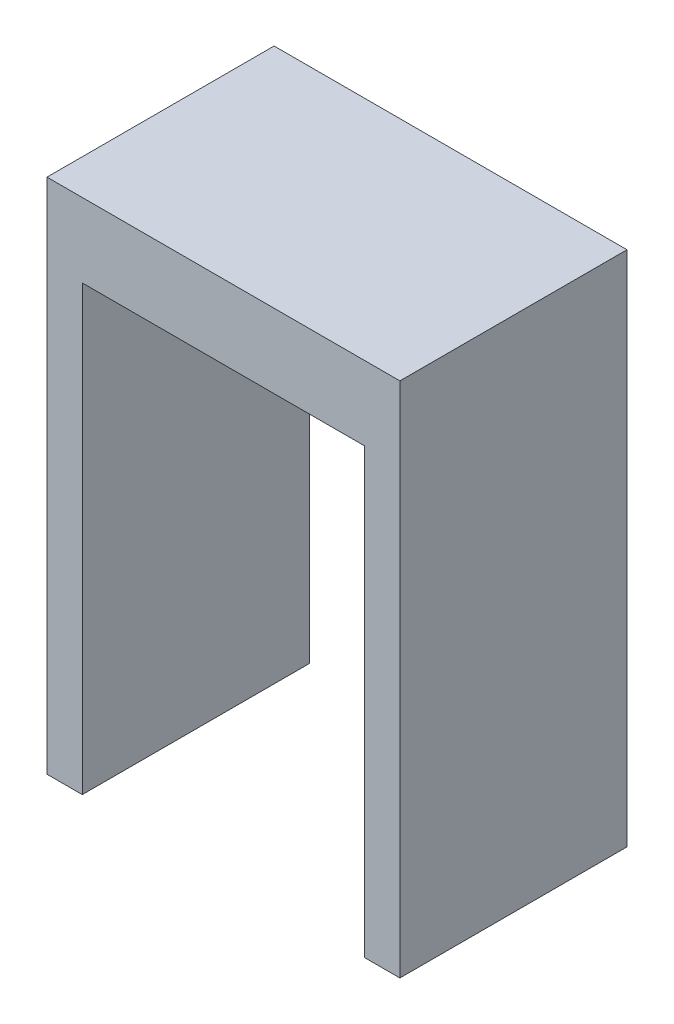
SolidWorks part; units mm, degrees
material "TPU"
ref_plane "Front Plane" through (0, 0, 0) normal (0, 0, 1) x (1, 0, 0)
ref_plane "Top Plane" through (0, 0, 0) normal (0, 1, 0) x (1, 0, 0)
ref_plane "Right Plane" through (0, 0, 0) normal (1, 0, 0) x (0, 0, -1)
sketch "Sketch1" plane through (0, 0, 0) normal (0, 0, 1) x (1, 0, 0)
  line L1 (-9.75, -13) -> (9.75, -13)
  line L2 (-9.75, -13) -> (-9.75, 13)
  line L3 (-9.75, 13) -> (9.75, 13)
  line L4 (9.75, -13) -> (9.75, 13)
  line L5 (-9.75, -13) -> (9.75, 13) construction
  line L6 (-9.75, 13) -> (9.75, -13) construction
  line L11 (-6.533, -8.7106) -> (32.8535, 43.8047) construction
  line L12 (-23.2087, 23.2087) -> (23.2087, -23.2087) construction
  point P0 (0, 0)
  point P6 (0, 0)
  dimension "D1" = 19.5
  dimension "D2" = 26
extrude "Boss-Extrude1" add sketch "Sketch1" along normal blind 10
sketch "Sketch2" plane through (0, 0, 10) normal (0, 0, 1) x (1, 0, 0)
  line L1 (-7.8, -10.4) -> (7.8, -10.4)
  line L2 (-7.8, -10.4) -> (-7.8, 10.4)
  line L3 (-7.8, 10.4) -> (7.8, 10.4)
  line L4 (7.8, -10.4) -> (7.8, 10.4)
  line L5 (-7.8, -10.4) -> (7.8, 10.4) construction
  line L6 (-7.8, 10.4) -> (7.8, -10.4) construction
  point P0 (0, 0)
  dimension "D1" = 15.6
  dimension "D2" = 20.8
extrude "Cut-Extrude1" cut sketch "Sketch2" against normal up to next
sketch "Sketch3" plane through (0, -13, 0) normal (0, -1, 0) x (1, 0, 0)
  line L0 (-9.75, 5) -> (-5.85, 5) construction
  line L1 (-9.75, 10) -> (-9.75, 0) construction
  line L2 (9.75, 5) -> (5.85, 5) construction
  line L3 (9.75, 10) -> (9.75, 0) construction
  circle A0 centre (-5.85, 5) radius 1.25
  circle A1 centre (5.85, 5) radius 1.25
  dimension "D3" = 2.5
  dimension "D4" = 2.5
  dimension "D1" = 3.9
  dimension "D2" = 3.9
extrude "Cut-Extrude2" cut sketch "Sketch3" against normal up to next
sketch "Sketch5" plane through (0, 13, 0) normal (0, 1, 0) x (1, 0, 0)
  line L0 (-9.75, -5) -> (-5.85, -5) construction
  line L1 (-9.75, -10) -> (-9.75, 0) construction
  line L2 (9.75, -5) -> (5.85, -5) construction
  line L3 (9.75, -10) -> (9.75, 0) construction
  circle A0 centre (-5.85, -5) radius 1.25
  circle A1 centre (5.85, -5) radius 1.25
  dimension "D3" = 2.5
  dimension "D1" = 3.9
  dimension "D2" = 3.9
sketch "Sketch6" plane through (0, 0, 10) normal (0, 0, 1) x (1, 0, 0)
  line L0 (9.75, -13) -> (9.75, 13) construction
  line L1 (-9.75, 13) -> (9.75, 13)
  line L2 (-9.75, 13) -> (-9.75, -1.2875)
  line L3 (-9.75, -1.2875) -> (9.75, -1.2875)
  line L4 (9.75, 13) -> (9.75, -1.2875)
  line L5 (-9.75, -1.2875) -> (-9.75, -13)
  line L6 (-9.75, -13) -> (9.75, -13)
  line L7 (9.75, -13) -> (9.75, -1.2875)
  line L8 (-9.75, -1.2875) -> (9.75, -1.2875)
  line L9 (-9.75, -1.2875) -> (-9.75, -13)
  line L10 (9.75, -1.2875) -> (9.75, -13)
  line M3 (7.8, 10.4) -> (7.8, -10.4)
  line M4 (7.8, -10.4) -> (-7.8, -10.4)
  line M5 (-7.8, -10.4) -> (-7.8, 10.4)
  line M6 (9.75, -13) -> (9.75, 13)
  line M8 (-9.75, 13) -> (-9.75, -13)
  line M9 (-9.75, -13) -> (9.75, -13)
  dimension "D1" = 14.2875
extrude "Cut-Extrude5" cut sketch "Sketch6" against normal blind 10 contours L3 M8 M9 M6 M3 M4 M5
sketch "Sketch8" plane through (0, 13, 0) normal (0, 1, 0) x (1, 0, 0)
  line L1 (-9.75, 0) -> (9.75, 0)
  line L2 (-9.75, 0) -> (-9.75, -10)
  line L3 (-9.75, -10) -> (9.75, -10)
  line L4 (9.75, 0) -> (9.75, -10)
extrude "Boss-Extrude2" add sketch "Sketch8" along normal blind 1.4875
sketch "Sketch9" plane through (0, 0, 10) normal (0, 0, 1) x (1, 0, 0)
  line L0 (-9.75, 14.4875) -> (-9.75, 0.2)
  line L2 (-9.75, 14.4875) -> (-9.75, -1.2875) construction
  line L3 (-9.75, 0.2) -> (9.75, 0.2)
  line L4 (9.75, -1.2875) -> (9.75, 14.4875) construction
  line L5 (9.75, 0.2) -> (9.75, -1.2875)
  line L6 (9.75, -1.2875) -> (-9.75, -1.2875)
  line L7 (-9.75, -1.2875) -> (-9.75, 0.2)
  line M3 (-9.75, -1.2875) -> (-7.8, -1.2875)
  line M4 (-7.8, -1.2875) -> (-7.8, 10.4)
  line M6 (7.8, 10.4) -> (7.8, -1.2875)
  line M7 (7.8, -1.2875) -> (9.75, -1.2875)
  line M8 (9.75, -1.2875) -> (9.75, 14.4875)
  line M10 (-9.75, 14.4875) -> (-9.75, -1.2875)
  dimension "D1" = 14.2875
extrude "Cut-Extrude7" cut sketch "Sketch9" against normal through all contours L6 L3 M6 M4 | L3 M6 M7 M8 | L3 M10 M3 M4
sketch "Sketch10" plane through (0, 0.2, 0) normal (0, -1, 0) x (1, 0, 0)
  line L0 (10.725, 0) -> (-10.725, 0) construction
  line L1 (-9.75, 10) -> (-7.8, 10)
  line L2 (-9.75, 10) -> (-9.75, 0)
  line L3 (-9.75, 0) -> (-7.8, 0)
  line L4 (-7.8, 10) -> (-7.8, 0)
  line L5 (-7.8, 0) -> (-7.8, 10) construction
  line L6 (7.8, 10) -> (7.8, 0) construction
  line L7 (9.75, 10) -> (7.8, 10)
  line L8 (9.75, 10) -> (9.75, 0)
  line L9 (9.75, 0) -> (7.8, 0)
  line L10 (7.8, 10) -> (7.8, 0)
extrude "Boss-Extrude3" add sketch "Sketch10" along normal blind 14.2875
sketch "Sketch11" plane through (0, 0, 10) normal (0, 0, 1) x (1, 0, 0)
  line L0 (-9.75, -14.0875) -> (-9.75, 14.4875)
  line L1 (-9.75, 14.4875) -> (9.75, 14.4875)
  line L2 (9.75, 14.4875) -> (9.75, -14.0875)
  line L3 (9.75, -14.0875) -> (7.8, -14.0875)
  line L4 (7.8, -14.0875) -> (7.8, 10.4)
  line L5 (7.8, 10.4) -> (-7.8, 10.4)
  line L6 (-7.8, 10.4) -> (-7.8, -14.0875)
  line L7 (-7.8, -14.0875) -> (-9.75, -14.0875)
extrude "Boss-Extrude4" add sketch "Sketch11" along normal blind 2.55
equation "\"Mount Width\"= 19.5mm"
equation "\"Mount Inner Size\"= \"Mount Width\" * 0.80"
equation "\"D1@Sketch1\"=\"Mount Width\""
equation "\"D1@Sketch3\"=\"Mount Width\"*0.2"
equation "\"D2@Sketch3\"=\"Mount Width\"*0.2"
equation "\"Hole Dim\"= 2.5mm"
equation "\"D3@Sketch3\"=\"Hole Dim\""
equation "\"D4@Sketch3\"=\"Hole Dim\""
equation "\"D1@Sketch5\"=\"Mount Width\"*0.2"
equation "\"D2@Sketch5\"=\"Mount Width\"*0.2"
equation "\"D3@Sketch5\"=\"Hole Dim\""
equation "\"Mount Height\"= 26mm"
equation "\"D2@Sketch1\"=\"Mount Height\""
equation "\"D1@Sketch2\"=\"Mount Width\" * 0.8"
equation "\"D2@Sketch2\"=\"Mount Height\" * 0.8"
